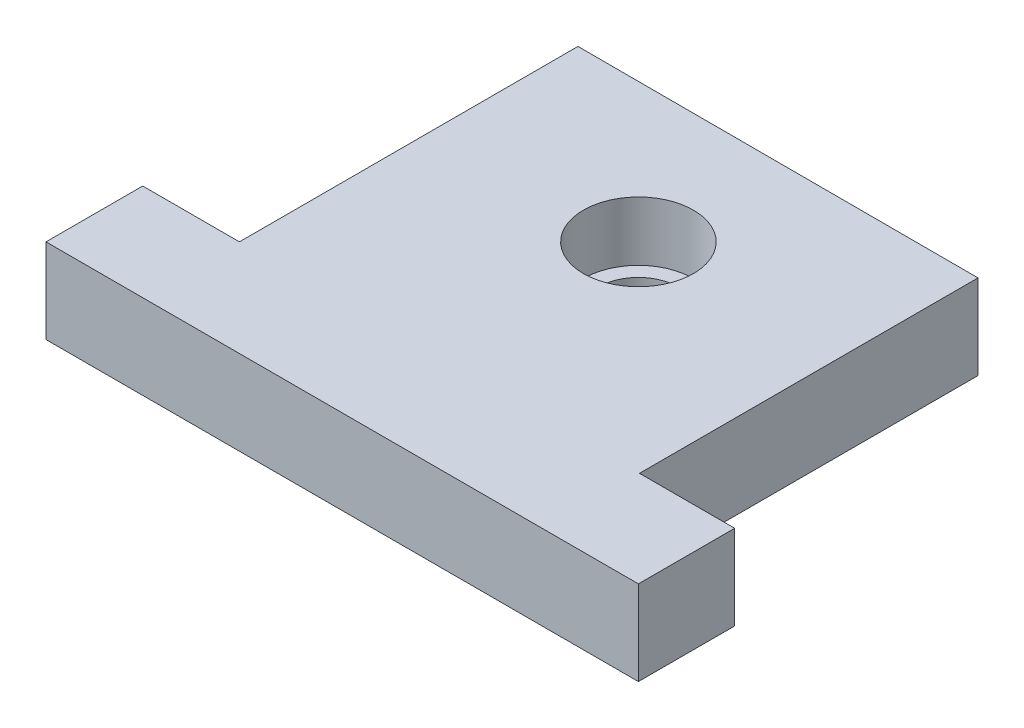
SolidWorks part; units mm, degrees
ref_plane "Front Plane" through (0, 0, 0) normal (0, 0, 1) x (1, 0, 0)
ref_plane "Top Plane" through (0, 0, 0) normal (0, 1, 0) x (1, 0, 0)
ref_plane "Right Plane" through (0, 0, 0) normal (1, 0, 0) x (0, 0, -1)
sketch "Sketch1" plane through (0, 0, 0) normal (0, 1, 0) x (1, 0, 0)
  line L0 (-35, 0) -> (35, 0)
  line L1 (-35, 0) -> (-35, 11.4286)
  line L2 (35, 0) -> (35, 11.3771)
  line L3 (-35, 11.4286) -> (-23.5714, 11.4286)
  line L4 (35, 11.3771) -> (23.7521, 11.3771)
  line L5 (-23.5714, 11.4286) -> (-23.5714, 51.4286)
  line L6 (23.7521, 11.3771) -> (23.7521, 51.3771)
  line L7 (-23.5714, 51.4286) -> (23.7521, 51.3771)
  line L8 (23.7521, 51.3771) -> (23.7356, 51.4618)
  point P4 (0, 0)
  dimension "D1" = 40
  dimension "D2" = 70
extrude "Boss-Extrude1" add sketch "Sketch1" along normal blind 10 contours L7 L5 L3 L1 L0 L2 L4 L6
sketch "Sketch2" plane through (0, 10, 0) normal (0, 1, 0) x (1, 0, 0)
  line L0 (-35, 0) -> (35, 0) construction
  circle A0 centre (0, 35) radius 6.5
  dimension "D1" = 35
  dimension "D2" = 13
extrude "Cut-Extrude2" cut sketch "Sketch2" against normal blind 7
sketch "Sketch5" plane through (0, 3, 0) normal (0, 1, 0) x (1, 0, 0)
  circle A0 centre (0, 35) radius 4.75
  dimension "D1" = 9.5
extrude "Cut-Extrude3" cut sketch "Sketch5" against normal through all
